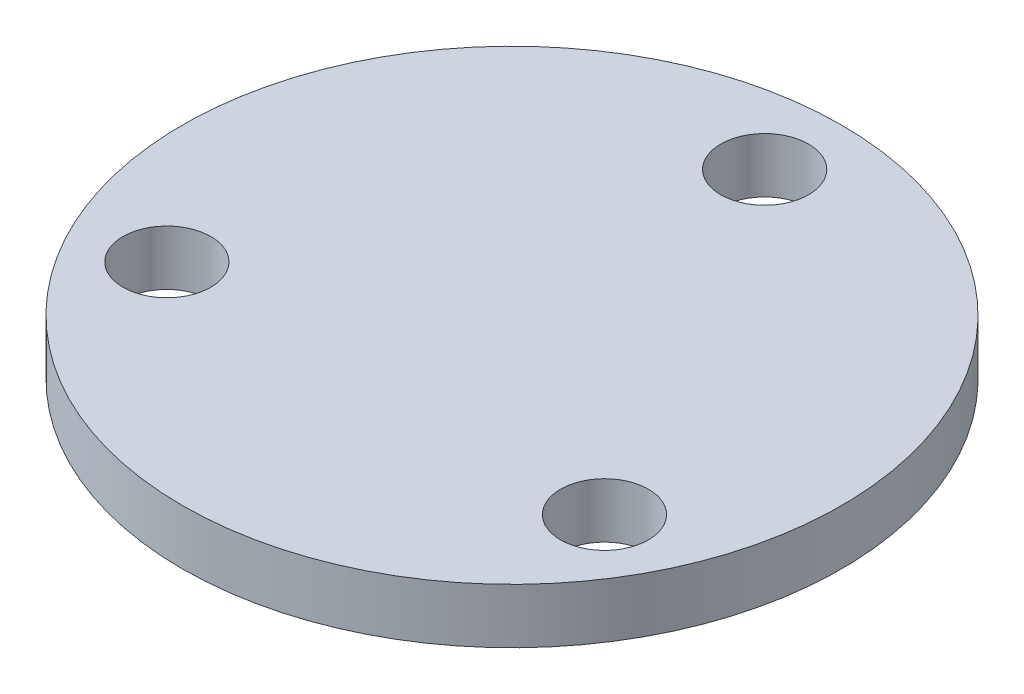
SolidWorks part; units mm, degrees
material "A286 铁基超合金"
ref_plane "前视基准面" through (0, 0, 0) normal (0, 0, 1) x (1, 0, 0)
ref_plane "上视基准面" through (0, 0, 0) normal (0, 1, 0) x (1, 0, 0)
ref_plane "右视基准面" through (0, 0, 0) normal (1, 0, 0) x (0, 0, -1)
sketch "草图1" plane through (0, 0, 0) normal (0, 1, 0) x (1, 0, 0)
  circle A0 centre (0, 0) radius 30
  circle A2 centre (0, 23) radius 4
  circle A3 centre (19.9186, -11.5) radius 4
  circle A4 centre (-19.9186, -11.5) radius 4
  point P12 (0, 0)
  dimension "D1" = 3
extrude "凸台-拉伸1" add sketch "草图1" along normal blind 5
